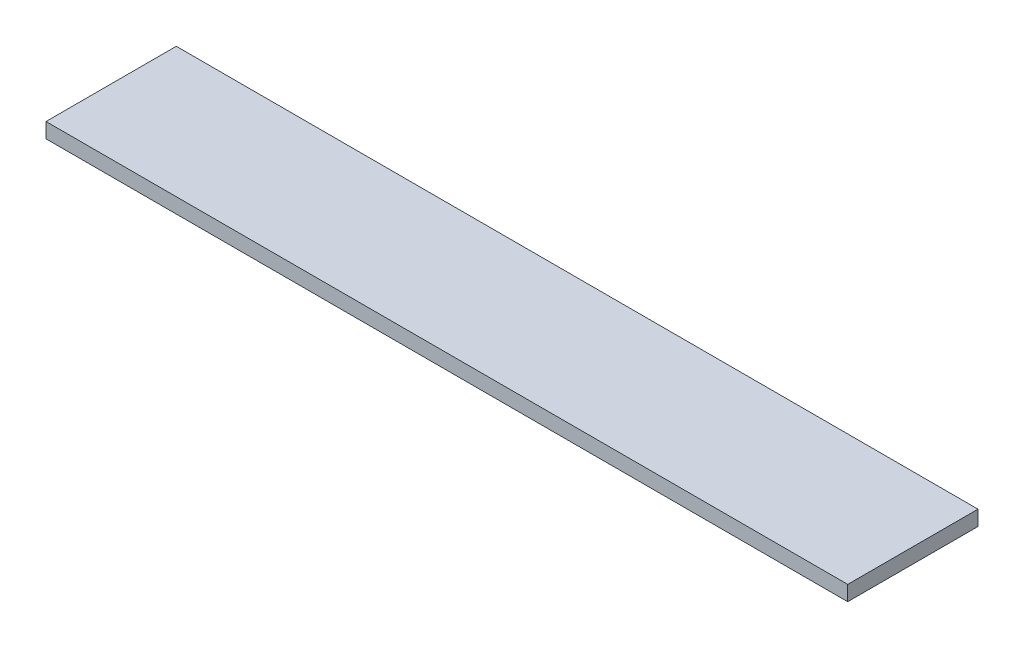
SolidWorks part; units mm, degrees
ref_plane "Front Plane" through (0, 0, 0) normal (0, 0, 1) x (1, 0, 0)
ref_plane "Top Plane" through (0, 0, 0) normal (0, 1, 0) x (1, 0, 0)
ref_plane "Right Plane" through (0, 0, 0) normal (1, 0, 0) x (0, 0, -1)
sketch "Sketch1" plane through (0, 0, 0) normal (0, 1, 0) x (1, 0, 0)
  line L1 (-143.8052, -936.4802) -> (872.1948, -936.4802)
  line L2 (-143.8052, -936.4802) -> (-143.8052, -771.3802)
  line L3 (-143.8052, -771.3802) -> (872.1948, -771.3802)
  line L4 (872.1948, -936.4802) -> (872.1948, -771.3802)
  dimension "D1" = 165.1
  dimension "D2" = 1016
extrude "Boss-Extrude1" add sketch "Sketch1" along normal blind 19.05
